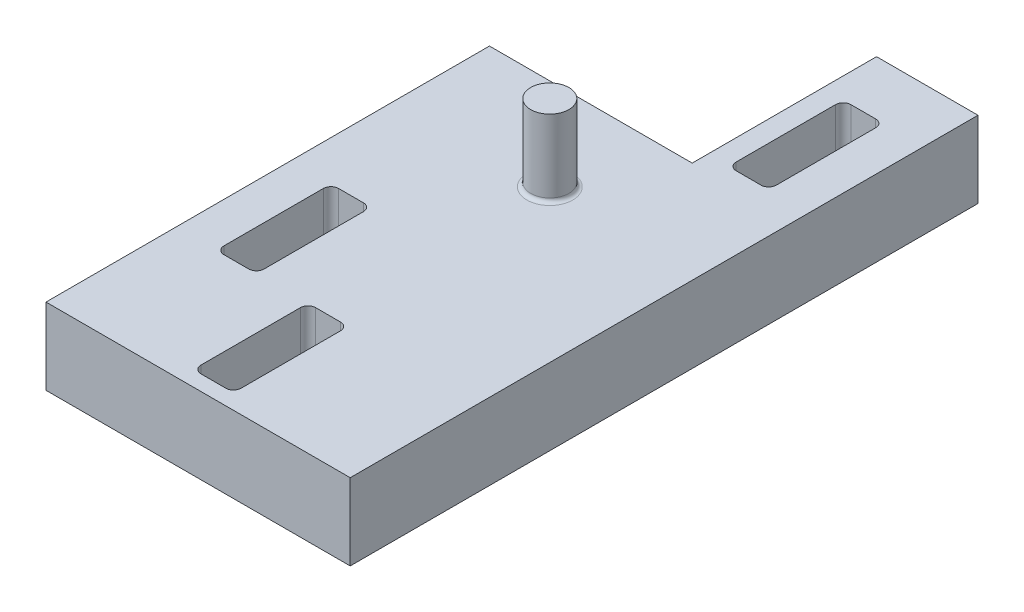
SolidWorks part; units mm, degrees
ref_plane "Front Plane" through (0, 0, 0) normal (0, 0, 1) x (1, 0, 0)
ref_plane "Top Plane" through (0, 0, 0) normal (0, 1, 0) x (1, 0, 0)
ref_plane "Right Plane" through (0, 0, 0) normal (1, 0, 0) x (0, 0, -1)
sketch "10" plane through (0, 0, 0) normal (0, 1, 0) x (1, 0, 0)
  line L0 (-15, 31.5) -> (15, 31.5) construction
  line L1 (-14.8938, 29.7182) -> (14.8938, 33.2818)
  line L2 (-14.8938, 29.7182) -> (-12, 15)
  line L3 (14.8938, 33.2818) -> (12, 48)
  line L4 (-12, 15) -> (0, 15)
  line L5 (12, 48) -> (0, 48)
  line L6 (0, 48) -> (0, 63)
  line L7 (0, 15) -> (0, 0)
  point P4 (0, 31.5)
  point P5 (0, 31.5)
  dimension "D1" = 15
  dimension "D2" = 12
  dimension "D3" = 15
  dimension "D4" = 30
  dimension "D5" = 30
  dimension "D6" = 15
  dimension "D7" = 0
  dimension "D8" = 0
  dimension "D9" = 31.5
sketch "01" plane through (0, 0, 0) normal (0, 1, 0) x (1, 0, 0)
  line L0 (-15, 31.5) -> (15, 31.5) construction
  line L1 (-9.3393, 19.7621) -> (9.3393, 43.2379)
  line L2 (-9.3393, 19.7621) -> (-12, 5)
  line L3 (9.3393, 43.2379) -> (12, 58)
  line L4 (-12, 5) -> (0, 5)
  line L5 (12, 58) -> (0, 58)
  line L6 (0, 58) -> (0, 73)
  line L7 (0, 5) -> (0, -10)
  point P4 (0, 31.5)
  point P5 (0, 31.5)
  dimension "D1" = 30
  dimension "D2" = 15
  dimension "D3" = 12
  dimension "D4" = 15
  dimension "D5" = 30
  dimension "D6" = 0
  dimension "D7" = 41.5
  dimension "D8" = 0
  dimension "D9" = 15
sketch "Sketch2" plane through (0, 0, 0) normal (0, 1, 0) x (1, 0, 0)
  line L1 (-19.8938, 77.5) -> (0, 77.5)
  line L2 (-19.8938, 77.5) -> (-19.8938, -14.5)
  line L3 (-19.8938, -14.5) -> (0, -14.5)
  line L9 (-15, 31.5) -> (15, 31.5) construction
  line L24 (0, 77.5) -> (0, 75.5)
  line L25 (-2.625, 73) -> (-2.625, 63)
  line L26 (0, 75.5) -> (-2.625, 75.5)
  line L27 (-2.625, 75.5) -> (-2.625, 73)
  line L28 (0, 60.5) -> (-2.625, 60.5)
  line L29 (-2.625, 60.5) -> (-2.625, 63)
  line L32 (0, 60.375) -> (0, 2.5)
  line L34 (0, 60.5) -> (0, 60.375)
  line L35 (-2.625, 0) -> (-2.625, -10)
  line L36 (0, 2.5) -> (-2.625, 2.5)
  line L37 (-2.625, 2.5) -> (-2.625, 0)
  line L38 (0, -12.5) -> (-2.625, -12.5)
  line L39 (-2.625, -12.5) -> (-2.625, -10)
  line L41 (0, -12.5) -> (0, -14.5)
  circle A7 centre (-14.8938, 29.7182) radius 5 construction
  circle A19 centre (0, 73) radius 2.625 construction
  circle A21 centre (0, 63) radius 2.625 construction
  circle A22 centre (0, 73) radius 2.5 construction
  circle A23 centre (0, 63) radius 2.5 construction
  circle A24 centre (0, -10) radius 2.625 construction
  circle A25 centre (0, 0) radius 2.625 construction
  circle A26 centre (0, 0) radius 2.5 construction
  circle A27 centre (0, -10) radius 2.5 construction
  dimension "D2" = 5.25
  dimension "D3" = 5.25
  dimension "D4" = 5
  dimension "D5" = 5
  dimension "D8" = 10
  dimension "D7" = 10
  dimension "D9" = 5.25
  dimension "D12" = 5.25
  dimension "D14" = 5
  dimension "D15" = 5
  dimension "D6" = 2
  dimension "D10" = 19.8938
  dimension "D11" = 5
  dimension "D13" = 19.8938
  dimension "D16" = 10
  dimension "D17" = 2
  dimension "D18" = 57.875
extrude "Boss-Extrude1" add sketch "Sketch2" along normal blind 10 contours L2 L3 L41 L38 L39 L35 L37 L36 L32 L34 L28 L29 L25 L27 L26 L24 L1
fillet "Fillet2" radius 1 4 edges at (-2.625, 5, 12.5) (-2.625, 5, -2.5) (-2.625, 5, -60.5) (-2.625, 5, -75.5)
mirror "Mirror1" of "Fillet2", "Boss-Extrude1"
sketch "Sketch4" plane through (0, 0, 0) normal (0, 1, 0) x (1, 0, 0)
  line L0 (-14.625, 15) -> (-14.625, 5)
  line L1 (-9.375, 15) -> (-9.375, 5)
  line L2 (-12, 2.5) -> (-9.375, 2.5)
  line L3 (-9.375, 2.5) -> (-9.375, 5)
  line L4 (-12, 2.5) -> (-14.625, 2.5)
  line L5 (-14.625, 2.5) -> (-14.625, 5)
  line L6 (-12, 17.5) -> (-9.375, 17.5)
  line L7 (-9.375, 17.5) -> (-9.375, 15)
  line L9 (-12, 17.5) -> (-14.625, 17.5)
  line L10 (-14.625, 17.5) -> (-14.625, 15)
  line L12 (9.375, 58) -> (9.375, 48)
  line L13 (14.625, 58) -> (14.625, 48)
  line L16 (12, 60.5) -> (9.375, 60.5)
  line L17 (9.375, 60.5) -> (9.375, 58)
  line L19 (12, 60.5) -> (14.625, 60.5)
  line L20 (14.625, 60.5) -> (14.625, 58)
  line L21 (12, 45.5) -> (14.625, 45.5)
  line L22 (14.625, 45.5) -> (14.625, 48)
  line L23 (12, 45.5) -> (9.375, 45.5)
  line L24 (9.375, 45.5) -> (9.375, 48)
  circle A0 centre (-12, 5) radius 2.625 construction
  circle A1 centre (-12, 15) radius 2.625 construction
  circle A14 centre (-12, 15) radius 2.5 construction
  circle A15 centre (-12, 5) radius 2.5 construction
  circle A16 centre (12, 48) radius 2.625 construction
  circle A17 centre (12, 48) radius 2.5 construction
  circle A18 centre (12, 58) radius 2.5 construction
  circle A19 centre (12, 58) radius 2.625 construction
  dimension "D1" = 5.25
  dimension "D2" = 5
extrude "Cut-Extrude1" cut sketch "Sketch4" along normal through all
fillet "Fillet3" radius 1 8 edges at (9.375, 5, -45.5) (14.625, 5, -45.5) (9.375, 5, -60.5) (14.625, 5, -60.5) (-14.625, 5, -2.5) (-9.375, 5, -2.5) (-9.375, 5, -17.5) (-14.625, 5, -17.5)
sketch "Sketch5" plane through (0, 10, 0) normal (0, 1, 0) x (1, 0, 0)
  line L0 (-14.8938, 29.7182) -> (14.8938, 33.2818) construction
  circle A0 centre (0, 31.5) radius 2.5
  dimension "D1" = 5
extrude "Boss-Extrude2" add sketch "Sketch5" along normal blind 10
fillet "Fillet1" radius 0.5 1 edges at (0, 10, -34)
sketch "Sketch6" plane through (0, 10, 0) normal (0, 1, 0) x (1, 0, 0)
  line L0 (19.8938, 77.5) -> (19.8938, 67.6092)
  line L9 (19.8938, 77.5) -> (19.8938, -14.5) construction
  line L10 (19.8938, 67.6092) -> (6.6238, 67.6092)
  line L11 (6.6238, 67.6092) -> (6.6238, 43.5)
  line L13 (6.6238, 43.5) -> (-6.625, 43.5)
  line L15 (-19.8938, 77.5) -> (19.8938, 77.5) construction
  line L16 (-6.625, 90.9007) -> (-6.625, 43.5) construction
  line L17 (-6.625, 77.5) -> (19.8938, 77.5)
  line L18 (-6.625, 43.5) -> (-19.8938, 43.5)
  line L19 (-19.8938, 77.5) -> (-19.8938, -14.5) construction
  line L20 (-19.8938, 43.5) -> (-19.8938, 77.5)
  line L21 (-19.8938, 77.5) -> (-6.625, 77.5)
  dimension "D1" = 13.27
  dimension "D4" = 24.1092
extrude "Cut-Extrude2" cut sketch "Sketch6" against normal blind 10 contours L17 L0 L10 L11 L13 L18 L20 L21
